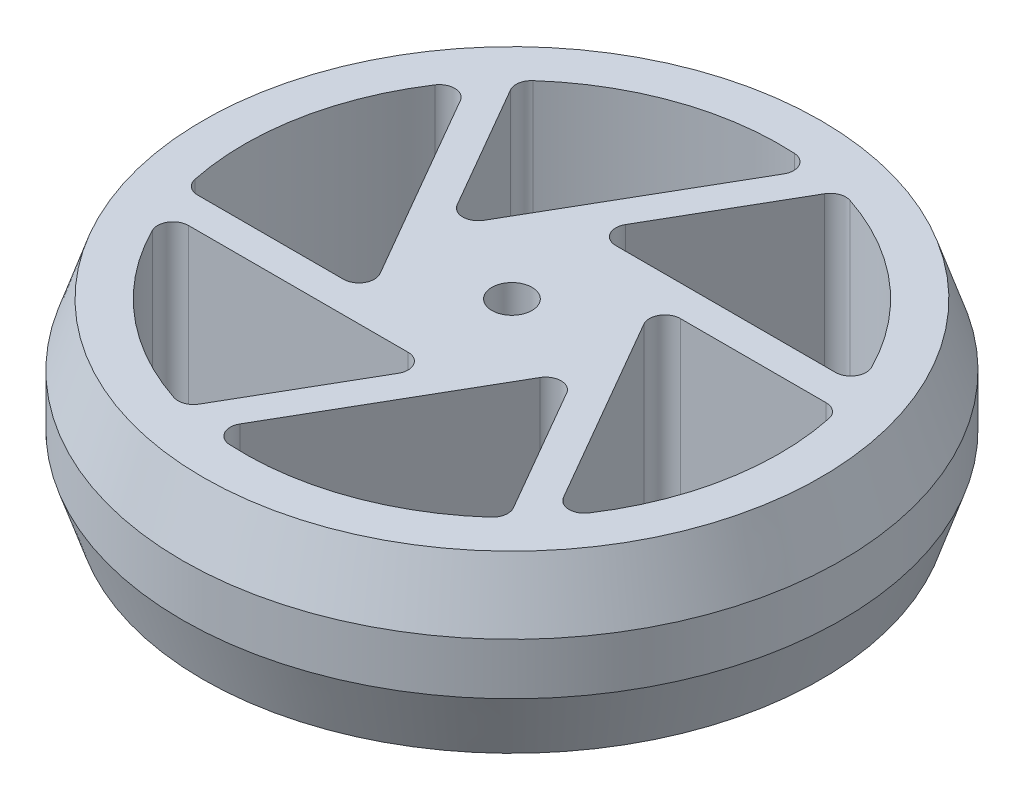
SolidWorks part; units mm, degrees
ref_plane "Front Plane" through (0, 0, 0) normal (0, 0, 1) x (1, 0, 0)
ref_plane "Top Plane" through (0, 0, 0) normal (0, 1, 0) x (1, 0, 0)
ref_plane "Right Plane" through (0, 0, 0) normal (1, 0, 0) x (0, 0, -1)
sketch "Sketch2" plane through (0, 0, 0) normal (0, 0, 1) x (1, 0, 0)
  line L0 (0, 0) -> (32, 0)
  line L1 (32, 0) -> (32, 2.5)
  line L2 (32, 2.5) -> (30, 8.5)
  line L3 (30, 8.5) -> (0, 8.5)
  line L4 (0, 8.5) -> (0, 0)
  point P3 (0, 0)
  point P7 (0, 8.5)
  point P9 (0, 7.7624)
  dimension "D1" = 2
  dimension "D2" = 8.5
  dimension "D3" = 32
  dimension "D4" = 2.5
revolve "Revolve1" add sketch "Sketch2" angle 360 about L4
mirror "Mirror1" about plane through (0, 0, 0) normal (0, 1, 0) of "Revolve1"
sketch "Sketch3" plane through (0, 0, 0) normal (0, 1, 0) x (1, 0, 0)
  line L0 (5.5, 9.5263) -> (24.1919, 9.5263)
  line L14 (-7.5359, 0) -> (6.9319, 25.0589)
  line L22 (5.5, 9.5263) -> (-5.5, 9.5263)
  line L23 (-5.5, 9.5263) -> (-11, 0)
  line L24 (-11, 0) -> (-5.5, -9.5263)
  line L25 (-5.5, -9.5263) -> (5.5, -9.5263)
  line L26 (5.5, -9.5263) -> (11, 0)
  line L27 (11, 0) -> (5.5, 9.5263)
  line L28 (-7.5359, 0) -> (-3.7679, -6.5263)
  line L29 (-3.7679, -6.5263) -> (3.7679, -6.5263)
  line L30 (3.7679, -6.5263) -> (7.5359, 0)
  line L31 (7.5359, 0) -> (3.7679, 6.5263)
  line L32 (3.7679, 6.5263) -> (-3.7679, 6.5263)
  line L33 (-3.7679, 6.5263) -> (-7.5359, 0)
  arc A0 (24.1919, 9.5263) -> (6.9319, 25.0589) centre (0, 0) ccw
  circle A2 centre (0, 0) radius 9.5263 construction
  circle A6 centre (0, 0) radius 26 construction
  arc A7 (8.1041, 24.7047) -> (6.3375, 24.0295) centre (7.6366, 23.2795) ccw
  arc A8 (21.8786, 9.5263) -> (23.2181, 11.7014) centre (21.8786, 11.0263) ccw
  arc A9 (-0.7369, 11.7763) -> (0.5622, 9.5263) centre (0.5622, 11.0263) ccw
  circle A10 centre (0, 0) radius 30 construction
  circle A11 centre (0, 0) radius 6.5263 construction
  dimension "D1" = 3
  dimension "D3" = 4
  dimension "D4" = 3
  dimension "D2" = 11
extrude "Cut-Extrude1" cut sketch "Sketch3" along normal up to surface and the other way up to surface contours L0 A0 L14 L22
pattern_circular "CirPattern1" count 6 over 360 about axis through (0, 0, 0) along (0, 1, 0) of "Cut-Extrude1"
sketch "Sketch6" plane through (0, 0, 0) normal (0, 1, 0) x (1, 0, 0)
  circle A0 centre (0, 0) radius 1.95
  dimension "D1" = 3.9
extrude "Cut-Extrude2" cut sketch "Sketch6" along normal blind 15 and the other way blind 15
